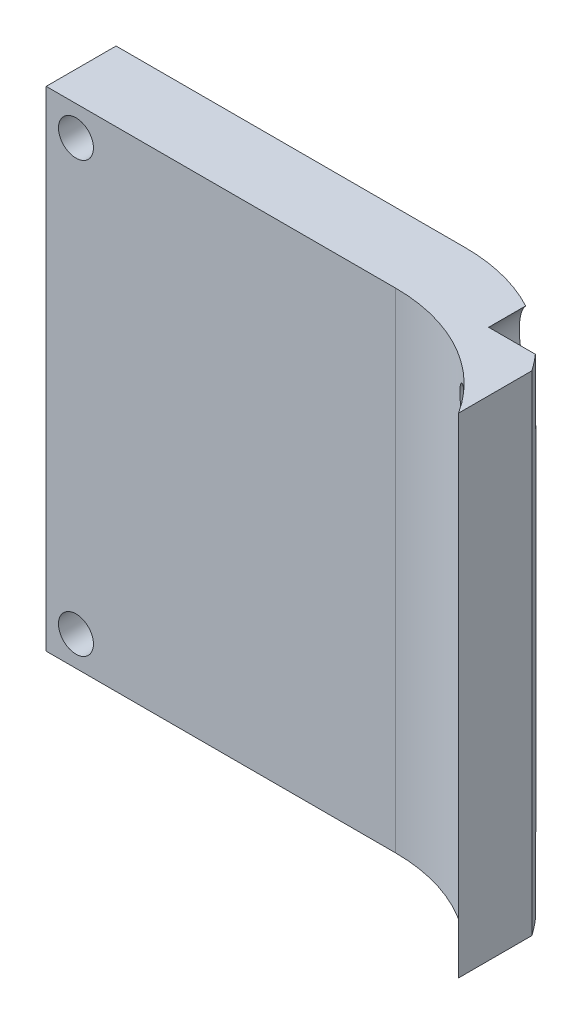
SolidWorks part; units mm, degrees
ref_plane "Alzado" through (0, 0, 0) normal (0, 0, 1) x (1, 0, 0)
ref_plane "Planta" through (0, 0, 0) normal (0, 1, 0) x (1, 0, 0)
ref_plane "Vista lateral" through (0, 0, 0) normal (1, 0, 0) x (0, 0, -1)
sketch "Croquis1" plane through (0, 0, 0) normal (0, 0, 1) x (1, 0, 0)
  line L0 (17.5, -17.5) -> (17.5, -15.37) construction
  line L1 (17.5, -17.5) -> (-17.5, -17.5)
  line L2 (17.5, -17.5) -> (17.5, 17.5)
  line L3 (17.5, 17.5) -> (-17.5, 17.5)
  line L4 (-17.5, -17.5) -> (-17.5, 17.5)
  line L5 (17.5, -17.5) -> (-17.5, 17.5) construction
  line L6 (17.5, 17.5) -> (-17.5, -17.5) construction
  line L7 (17.5, -15.37) -> (15.37, -15.37) construction
  line L8 (-17.5, -15.37) -> (-15.37, -15.37) construction
  line L9 (-15.37, 17.5) -> (-15.37, 15.37) construction
  line L10 (15.37, 17.5) -> (15.37, 15.37) construction
  circle A0 centre (15.37, -15.37) radius 1.25
  circle A1 centre (-15.37, -15.37) radius 1.25
  circle A2 centre (-15.37, 15.37) radius 1.25
  circle A3 centre (15.37, 15.37) radius 1.25
  point P0 (0, 0)
  dimension "D4" = 2.5
  dimension "D6" = 2.5
  dimension "D7" = 2.13
  dimension "D8" = 2.5
  dimension "D10" = 2.5
  dimension "D1" = 35
  dimension "D2" = 2.13
  dimension "D3" = 2.13
  dimension "D5" = 2.13
  dimension "D9" = 2.13
extrude "Saliente-Extruir1" add sketch "Croquis1" along normal blind 5
sketch "Croquis2" plane through (0, 17.5, 0) normal (0, 1, 0) x (1, 0, 0)
  line L0 (17.5, -5) -> (17.5, -10.5)
  line L1 (17.5, -5) -> (7.5, -5)
  line L2 (17.5, -5) -> (-17.5, -5) construction
  line L3 (17.5, 0) -> (7.5, 0)
  line L4 (17.5, 0) -> (-17.5, 0) construction
  line L5 (7.5, 0) -> (17.5, 0)
  line L6 (17.5, -5) -> (17.5, 0)
  arc A0 (7.5, -5) -> (17.5, -10.5) centre (7.5, -16.8409) cw
  arc A1 (7.5, 0) -> (17.5, -5) centre (7.5, -12.5) cw
  dimension "D1" = 5.5
  dimension "D2" = 10
extrude "Saliente-Extruir2" add sketch "Croquis2" against normal through all contours A0 L0 L1
sketch "Croquis3" plane through (0, 17.5, 0) normal (0, 1, 0) x (1, 0, 0)
  line L0 (17.5, 0) -> (7.5, 0)
  line L1 (17.5, 0) -> (-17.5, 0) construction
  line L2 (17.5, -10.5) -> (17.5, 0) construction
  line L3 (17.5, 0) -> (17.5, -5.25)
  arc A0 (7.5, 0) -> (17.5, -5.25) centre (7.5, -12.1488) cw
  dimension "D1" = 10
extrude "Cortar-Extruir2" cut sketch "Croquis3" against normal through all and the other way through all
sketch "Croquis4" plane through (0, 0, 5) normal (0, 0, -1) x (-1, 0, 0)
  circle A0 centre (-15.37, 15.37) radius 1.25
  circle A1 centre (-15.37, -15.37) radius 1.25
extrude "Cortar-Extruir3" cut sketch "Croquis4" against normal blind 10
sketch "Croquis5" plane through (0, 0, 0) normal (0, 0, -1) x (-1, 0, 0)
  circle A0 centre (-15.37, 15.37) radius 3
  circle A1 centre (-15.37, -15.37) radius 3
  dimension "D1" = 6
  dimension "D2" = 3
extrude "Cortar-Extruir6" cut sketch "Croquis5" against normal blind 4.1
